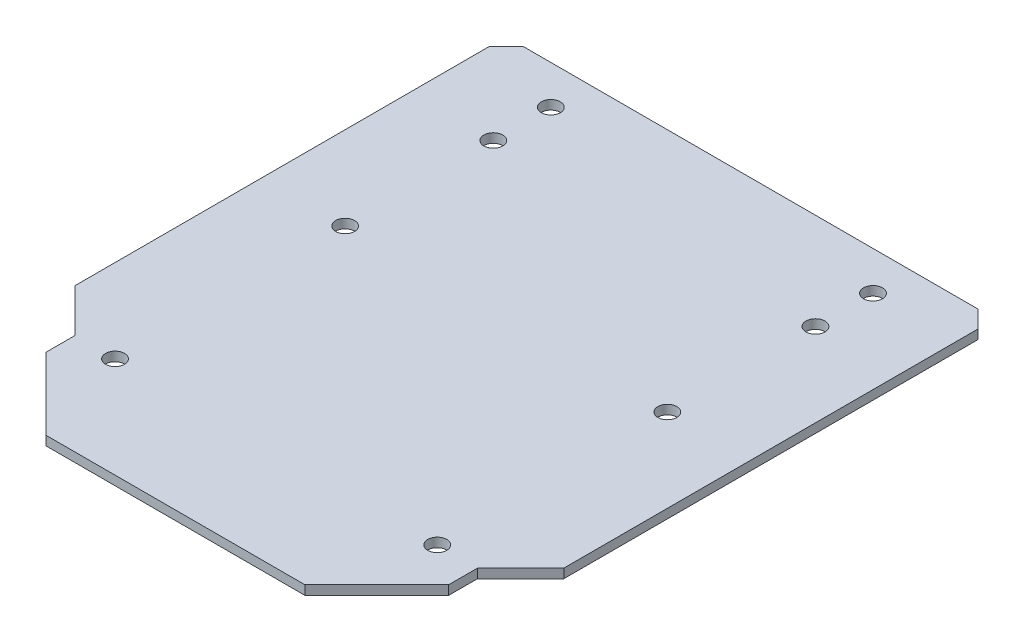
SolidWorks part; units mm, degrees
ref_plane "前视基准面" through (0, 0, 0) normal (0, 0, 1) x (1, 0, 0)
ref_plane "上视基准面" through (0, 0, 0) normal (0, 1, 0) x (1, 0, 0)
ref_plane "右视基准面" through (0, 0, 0) normal (1, 0, 0) x (0, 0, -1)
sketch "草图1" plane through (0, 0, 0) normal (0, 1, 0) x (1, 0, 0)
  line L1 (-42.5, -37.5) -> (42.5, -37.5)
  line L2 (-42.5, -37.5) -> (-42.5, 37.5)
  line L3 (-42.5, 37.5) -> (42.5, 37.5)
  line L4 (42.5, -37.5) -> (42.5, 37.5)
  line L5 (-42.5, -37.5) -> (42.5, 37.5) construction
  line L6 (-42.5, 37.5) -> (42.5, -37.5) construction
  point P0 (0, 0)
  dimension "D1" = 85
  dimension "D2" = 75
extrude "凸台-拉伸1" add sketch "草图1" along normal blind 1.6
sketch "草图2" plane through (0, 1.6, 0) normal (0, 1, 0) x (1, 0, 0)
  line L1 (-28, -20) -> (28, -20) construction
  line L2 (-28, -20) -> (-28, 20) construction
  line L3 (-28, 20) -> (28, 20) construction
  line L4 (28, -20) -> (28, 20) construction
  line L5 (-28, -20) -> (28, 20) construction
  line L6 (-28, 20) -> (28, -20) construction
  circle A0 centre (-28, 20) radius 1.65
  circle A1 centre (-28, -20) radius 1.65
  circle A2 centre (28, 20) radius 1.65
  circle A3 centre (28, -20) radius 1.65
  point P0 (0, 0)
  dimension "D3" = 3.3
  dimension "D1" = 56
  dimension "D2" = 40
extrude "切除-拉伸1" cut sketch "草图2" against normal up to next
sketch "草图8" plane through (0, 0, 0) normal (0, 1, 0) x (1, 0, 0)
  line L0 (42.5, -37.5) -> (42.5, 37.5) construction
  line L1 (-42.5, 37.5) -> (42.5, 37.5)
  line L2 (-42.5, 37.5) -> (-42.5, 62.5)
  line L3 (-42.5, 62.5) -> (42.5, 62.5)
  line L4 (42.5, 37.5) -> (42.5, 62.5)
  dimension "D1" = 25
extrude "凸台-拉伸3" add sketch "草图8" along normal up to surface (1.6 mm away) up to face at (-28, 1.6, 21.65)
chamfer "倒角2" distance 3 angle 45 2 edges at (42.5, 0.8, -62.5) (-42.5, 0.8, -62.5)
chamfer "倒角3" distance 20 angle 45 2 edges at (42.5, 0.8, 37.5) (-42.5, 0.8, 37.5)
sketch "草图7" plane through (0, 1.6, 0) normal (0, 1, 0) x (1, 0, 0)
  line L0 (-35, -25) -> (-35, -20)
  line L1 (-42.5, -17.5) -> (-22.5, -37.5) construction
  line L2 (-35, -20) -> (-42.5, -12.5)
  line L3 (-42.5, 59.5) -> (-42.5, -17.5) construction
  line L4 (-42.5, -12.5) -> (-42.5, -17.5)
  line L5 (-42.5, -17.5) -> (-35, -25)
  dimension "D1" = 5
  dimension "D2" = 7.5
extrude "切除-拉伸4" cut sketch "草图7" against normal up to next
mirror "镜向1" about plane through (0, 0, 0) normal (1, 0, 0) of "切除-拉伸4"
sketch "草图9" plane through (0, 1.6, 0) normal (0, 1, 0) x (1, 0, 0)
  line L0 (0, 0) -> (0, 50.75) construction
  line L1 (0, -0.88) -> (0, 0.88) construction
  line L2 (-28, 20) -> (-28, 45.75) construction
  line L3 (-28, 45.75) -> (28, 45.75) construction
  line L4 (-28, 45.75) -> (-28, 55.75) construction
  line L5 (-28, 55.75) -> (28, 55.75) construction
  line L6 (28, 45.75) -> (28, 55.75) construction
  line L7 (-28, 45.75) -> (28, 55.75) construction
  line L8 (-28, 55.75) -> (28, 45.75) construction
  circle A0 centre (-28, 55.75) radius 1.65
  circle A1 centre (-28, 45.75) radius 1.65
  circle A2 centre (28, 55.75) radius 1.65
  circle A3 centre (28, 45.75) radius 1.65
  dimension "D3" = 3.3
  dimension "D1" = 10
  dimension "D2" = 25.75
extrude "切除-拉伸5" cut sketch "草图9" against normal up to next
